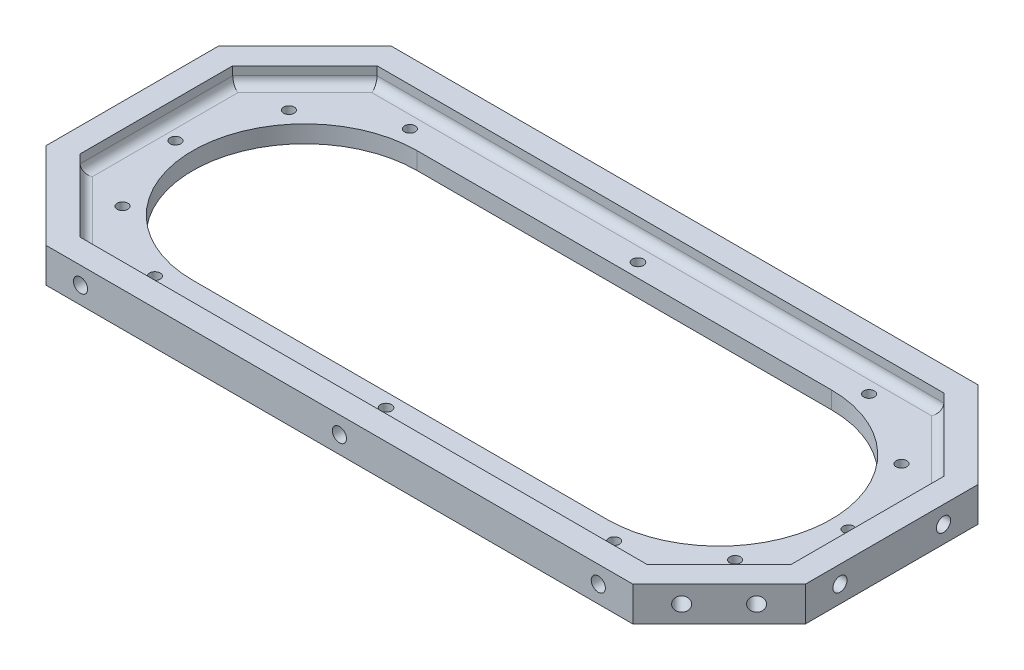
SolidWorks part; units mm, degrees
ref_plane "Front Plane" through (0, 0, 0) normal (0, 0, 1) x (1, 0, 0)
ref_plane "Top Plane" through (0, 0, 0) normal (0, 1, 0) x (1, 0, 0)
ref_plane "Right Plane" through (0, 0, 0) normal (1, 0, 0) x (0, 0, -1)
sketch "Sketch1" plane through (0, 0, 0) normal (0, 1, 0) x (1, 0, 0)
  line L1 (0, 0) -> (60, 0) construction
  line L3 (60, -75) -> (0, -75) construction
  line L7 (0, 12.5) -> (0, 0)
  line L9 (0, -75) -> (0, -87.5)
  line L10 (0, -115.7193) -> (0, -87.5) construction
  line L11 (0, -75) -> (0, -70)
  line L12 (0, 12.5) -> (85, 12.5)
  line L14 (85, 12.5) -> (110, -12.5)
  line L15 (110, -12.5) -> (110, -62.5)
  line L16 (110, -62.5) -> (85, -87.5)
  line L17 (0, -87.5) -> (85, -87.5)
  line L18 (60, -5) -> (0, -5)
  line L19 (60, -70) -> (0, -70)
  line L21 (0, -5) -> (0, 0)
  arc A0 (60, 0) -> (60, -75) centre (60, -37.5) cw construction
  arc A4 (60, -70) -> (60, -5) centre (60, -37.5) ccw
  dimension "D1" = 75
  dimension "D3" = 120
  dimension "D4" = 135
  dimension "D2" = 5
  dimension "D5" = 135
  dimension "D6" = 220
  dimension "D8" = 100
  dimension "D7" = 25
extrude "Main" add sketch "Sketch1" along normal blind 10
sketch "Sketch3" plane through (0, 10, 0) normal (0, 1, 0) x (1, 0, 0)
  arc A0 (60, -75) -> (60, 0) centre (60, -37.5) ccw construction
  arc A1 (60, -75) -> (60, 0) centre (60, -37.5) ccw construction
  circle A2 centre (97.5, -37.5) radius 1.55
  dimension "D1" = 3.1
extrude "Actuator Screw Hole" cut sketch "Sketch3" against normal through all
pattern_circular "Actuator Screw Hole Pattern" count 3 every 40 about axis through (60, 0, 37.5) along (0, 1, 0) of "Actuator Screw Hole"
fillet "Midspan fillet" [suppressed] radius 15
mirror "Mirror1" about plane through (0, 0, 0) normal (1, 0, 0) of bodies 103
sketch "Sketch7" plane through (0, 10, 0) normal (0, 1, 0) x (1, 0, 0)
  line L0 (0, -6.5) -> (0, -37.5) construction
  line L1 (110, -37.5) -> (-110, -37.5) construction
  line L2 (110, -12.5) -> (110, -62.5) construction
  line L3 (-85, 12.5) -> (85, 12.5) construction
  line L4 (-110, -12.5) -> (-110, -62.5) construction
  line L5 (0, -37.5) -> (0, -68.5) construction
  circle A0 centre (0, -68.5) radius 12
  circle A1 centre (0, -6.5) radius 12
  dimension "D1" = 24
  dimension "D2" = 7
extrude "Wire holes" [suppressed] cut sketch "Sketch7" against normal through all
sketch "Sketch8" plane through (0, 10, 0) normal (0, 1, 0) x (1, 0, 0)
  line L16 (82.1005, 5.5) -> (-82.1005, 5.5)
  line L17 (-82.1005, 5.5) -> (-103, -15.3995)
  line L18 (-103, -15.3995) -> (-103, -59.6005)
  line L19 (-103, -59.6005) -> (-82.1005, -80.5)
  line L20 (-82.1005, -80.5) -> (82.1005, -80.5)
  line L21 (82.1005, -80.5) -> (103, -59.6005)
  line L22 (103, -59.6005) -> (103, -15.3995)
  line L23 (103, -15.3995) -> (82.1005, 5.5)
  line L24 (82.1005, 5.5) -> (-82.1005, 5.5)
  line L25 (-82.1005, 5.5) -> (-103, -15.3995)
  line L26 (-103, -15.3995) -> (-103, -59.6005)
  line L27 (-103, -59.6005) -> (-82.1005, -80.5)
  line L28 (-82.1005, -80.5) -> (82.1005, -80.5)
  line L29 (82.1005, -80.5) -> (103, -59.6005)
  line L30 (103, -59.6005) -> (103, -15.3995)
  line L31 (103, -15.3995) -> (82.1005, 5.5)
  dimension "D1" = 7
extrude "Dish" cut sketch "Sketch8" against normal blind 5
fillet "Dish fillet" radius 2.5 8 edges at (0, 5, 80.5) (0, 5, -5.5) (92.5503, 5, 4.9497) (103, 5, 37.5) (92.5503, 5, 70.0503) (-92.5503, 5, 70.0503) (-103, 5, 37.5) (-92.5503, 5, 4.9497)
chamfer "Wire hole chamfer" [suppressed] distance 1 angle 45
sketch3d "3DSketch2"
  line L0 (-85, 5, 87.5) -> (-75, 5, 87.5) construction
  line L1 (-85, 10, 87.5) -> (-85, 0, 87.5) construction
  line L2 (-75, 5, 87.5) -> (0, 5, 87.5) construction
  line L3 (0, 5, 87.5) -> (75, 5, 87.5) construction
  line L4 (75, 5, 87.5) -> (85, 5, 87.5) construction
  line L5 (85, 10, 87.5) -> (85, 0, 87.5) construction
  line L6 (85, 5, 87.5) -> (92.0711, 5, 80.4289) construction
  line L7 (92.0711, 5, 80.4289) -> (102.9289, 5, 69.5711) construction
  line L8 (102.9289, 5, 69.5711) -> (110, 5, 62.5) construction
  line L9 (110, 10, 62.5) -> (110, 0, 62.5) construction
  line L10 (110, 5, 62.5) -> (110, 5, 52.5) construction
  line L11 (110, 5, 52.5) -> (110, 5, 22.5) construction
  line L12 (110, 5, 22.5) -> (110, 5, 12.5) construction
  line L13 (110, 10, 12.5) -> (110, 0, 12.5) construction
  line L14 (110, 5, 12.5) -> (102.9289, 5, 5.4289) construction
  line L15 (102.9289, 5, 5.4289) -> (92.0711, 5, -5.4289) construction
  line L16 (92.0711, 5, -5.4289) -> (85, 5, -12.5) construction
  line L17 (85, 10, -12.5) -> (85, 0, -12.5) construction
  line L18 (85, 5, -12.5) -> (75, 5, -12.5) construction
  line L19 (75, 5, -12.5) -> (0, 5, -12.5) construction
  line L20 (-75, 5, -12.5) -> (-85, 5, -12.5) construction
  line L21 (-85, 10, -12.5) -> (-85, 0, -12.5) construction
  line L22 (-85, 5, -12.5) -> (-92.0711, 5, -5.4289) construction
  line L23 (-92.0711, 5, -5.4289) -> (-102.9289, 5, 5.4289) construction
  line L24 (-102.9289, 5, 5.4289) -> (-110, 5, 12.5) construction
  line L25 (-110, 10, 12.5) -> (-110, 0, 12.5) construction
  line L26 (-110, 5, 12.5) -> (-110, 5, 22.5) construction
  line L27 (-110, 5, 22.5) -> (-110, 5, 52.5) construction
  line L28 (-110, 5, 52.5) -> (-110, 5, 62.5) construction
  line L29 (-110, 10, 62.5) -> (-110, 0, 62.5) construction
  line L30 (-110, 5, 62.5) -> (-102.9289, 5, 69.5711) construction
  line L31 (-102.9289, 5, 69.5711) -> (-92.0711, 5, 80.4289) construction
  line L32 (-92.0711, 5, 80.4289) -> (-85, 5, 87.5) construction
  line L33 (0, 5, -12.5) -> (-75, 5, -12.5) construction
  dimension "D1" = 10
  dimension "D2" = 10
  dimension "D3" = 10
hole_wizard "Ø4.0mm Dowel Hole1" positions "3DSketch5" profile "Sketch12" hole size "Ø4.0" standard "ANSI Metric"
sketch3d "3DSketch5"
  line L0 (85, 5, -12.5) -> (75, 5, -12.5) construction
  line L1 (85, 10, -12.5) -> (85, 0, -12.5) construction
  line L2 (75, 5, -12.5) -> (0, 5, -12.5) construction
  line L3 (0, 5, -12.5) -> (-75, 5, -12.5) construction
  line L4 (-75, 5, -12.5) -> (-85, 5, -12.5) construction
  line L5 (-85, 10, -12.5) -> (-85, 0, -12.5) construction
  line L6 (-85, 5, -12.5) -> (-92.0711, 5, -5.4289) construction
  line L7 (-92.0711, 5, -5.4289) -> (-102.9289, 5, 5.4289) construction
  line L8 (-102.9289, 5, 5.4289) -> (-110, 5, 12.5) construction
  line L9 (-110, 10, 12.5) -> (-110, 0, 12.5) construction
  line L10 (-110, 5, 12.5) -> (-110, 5, 22.5) construction
  line L11 (-110, 5, 22.5) -> (-110, 5, 52.5) construction
  line L12 (-110, 5, 52.5) -> (-110, 5, 62.5) construction
  line L13 (-110, 10, 62.5) -> (-110, 0, 62.5) construction
  line L14 (-110, 5, 62.5) -> (-102.9289, 5, 69.5711) construction
  line L15 (-102.9289, 5, 69.5711) -> (-92.0711, 5, 80.4289) construction
  line L16 (-92.0711, 5, 80.4289) -> (-85, 5, 87.5) construction
  line L17 (-85, 10, 87.5) -> (-85, 0, 87.5) construction
  line L18 (-85, 5, 87.5) -> (-75, 5, 87.5) construction
  line L19 (-75, 5, 87.5) -> (0, 5, 87.5) construction
  line L20 (0, 5, 87.5) -> (75, 5, 87.5) construction
  line L21 (75, 5, 87.5) -> (85, 5, 87.5) construction
  line L22 (85, 10, 87.5) -> (85, 0, 87.5) construction
  line L23 (85, 5, 87.5) -> (92.0711, 5, 80.4289) construction
  line L24 (92.0711, 5, 80.4289) -> (102.9289, 5, 69.5711) construction
  line L25 (102.9289, 5, 69.5711) -> (110, 5, 62.5) construction
  line L26 (110, 10, 62.5) -> (110, 0, 62.5) construction
  line L27 (110, 5, 62.5) -> (110, 5, 52.5) construction
  line L28 (110, 5, 52.5) -> (110, 5, 22.5) construction
  line L29 (110, 5, 22.5) -> (110, 5, 12.5) construction
  line L30 (110, 10, 12.5) -> (110, 0, 12.5) construction
  line L31 (110, 5, 12.5) -> (102.9289, 5, 5.4289) construction
  line L32 (102.9289, 5, 5.4289) -> (92.0711, 5, -5.4289) construction
  line L33 (92.0711, 5, -5.4289) -> (85, 5, -12.5) construction
  line L34 (110, 5, 12.5) -> (85, 5, -12.5) construction
  line L36 (-85, 5, -12.5) -> (-110, 5, 12.5) construction
  line L38 (-110, 5, 62.5) -> (-85, 5, 87.5) construction
  line L40 (85, 5, 87.5) -> (110, 5, 62.5) construction
  point P0 (75, 5, -12.5)
  point P2 (0, 5, -12.5)
  point P4 (-75, 5, -12.5)
  point P6 (-92.0711, 5, -5.4289)
  point P8 (-102.9289, 5, 5.4289)
  point P10 (-110, 5, 22.5)
  point P12 (-110, 5, 52.5)
  point P14 (-102.9289, 5, 69.5711)
  point P16 (-92.0711, 5, 80.4289)
  point P18 (-75, 5, 87.5)
  point P20 (0, 5, 87.5)
  point P22 (75, 5, 87.5)
  point P24 (92.0711, 5, 80.4289)
  point P26 (102.9289, 5, 69.5711)
  point P28 (110, 5, 52.5)
  point P30 (110, 5, 22.5)
  point P32 (102.9289, 5, 5.4289)
  point P34 (92.0711, 5, -5.4289)
  dimension "D1" = 10
  dimension "D2" = 10
  dimension "D3" = 10
sketch "Sketch12" plane through (75, 5, -12.5) normal (1, 0, 0) x (0, 1, 0)
  line L0 (0, 0) -> (0, 5.7)
  line L1 (0, 5.7) -> (2.05, 5.7)
  line L2 (2.05, 5.7) -> (2.05, 0)
  line L5 (2.05, 0) -> (0, 0)
  line L10 (0, 5.7) -> (-2.05, 5.7) construction
  line L11 (0, -6.35) -> (0, 107.95) construction
  dimension "Hole Dia." = 4.1
  dimension "Hole Depth" = 5.7
  dimension "Drill Angle" = 180
sketch "Sketch14" plane through (0, 0, 0) normal (0, -1, 0) x (1, 0, 0)
  line L0 (0, 1) -> (0, 5) construction
  line L4 (60, 5) -> (-60, 5) construction
  line L7 (-85, 87.5) -> (85, 87.5) construction
  line L8 (0, 74) -> (0, 70) construction
  line L9 (-85, 87.5) -> (85, 87.5) construction
  line L11 (60, 70) -> (-60, 70) construction
  circle A0 centre (0, 1) radius 1.6
  circle A1 centre (0, 74) radius 1.6
  dimension "D1" = 3.2
  dimension "D2" = 4
extrude "Cover srcrewholes" cut sketch "Sketch14" against normal through all
equation "\"length\" = 215mm"
equation "\"width\" = 220mm"
equation "\"height\" = 100mm"
equation "\"skin_th\" = 6mm"
equation "\"D6@Sketch1\"=\"width\""
equation "\"D8@Sketch1\"=\"height\""
